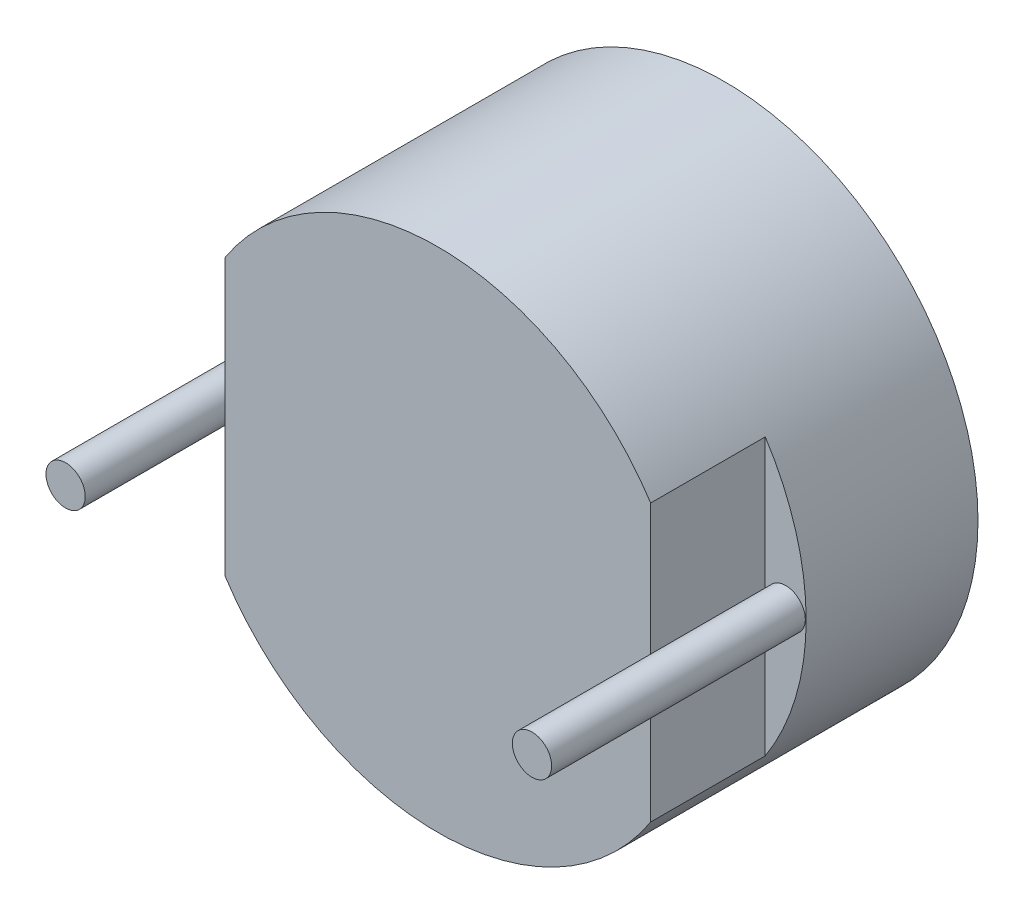
SolidWorks part; units mm, degrees
ref_plane "Front Plane" through (0, 0, 0) normal (0, 0, 1) x (1, 0, 0)
ref_plane "Top Plane" through (0, 0, 0) normal (0, 1, 0) x (1, 0, 0)
ref_plane "Right Plane" through (0, 0, 0) normal (1, 0, 0) x (0, 0, -1)
sketch "Sketch1" plane through (0, 0, 0) normal (0, 0, 1) x (1, 0, 0)
  circle A0 centre (-49.1532, 27.1636) radius 3.1
extrude "Boss-Extrude1" add sketch "Sketch1" along normal blind 3.5
sketch "Sketch2" plane through (0, 0, 3.5) normal (0, 0, 1) x (1, 0, 0)
  line L2 (-51.7532, 27.1636) -> (-51.7532, 28.8518)
  line L3 (-51.7532, 27.1636) -> (-51.7532, 25.4754)
  line L4 (-46.5532, 27.1636) -> (-46.5532, 25.4754)
  line L5 (-46.5532, 27.1636) -> (-46.5532, 28.8518)
  circle A0 centre (-49.1532, 27.1636) radius 3.1 construction
  arc A1 (-51.7532, 28.8518) -> (-51.7532, 25.4754) centre (-49.1532, 27.1636) ccw
  arc A2 (-46.5532, 25.4754) -> (-46.5532, 28.8518) centre (-49.1532, 27.1636) ccw
extrude "Cut-Extrude1" cut sketch "Sketch2" against normal blind 1.4
sketch "Sketch4" plane through (0, 0, 2.1) normal (0, 0, 1) x (1, 0, 0)
  circle A0 centre (-46.3032, 27.1636) radius 0.24
extrude "Boss-Extrude23" add sketch "Sketch4" along normal blind 3.1
sketch "Sketch5" plane through (0, 0, 2.1) normal (0, 0, 1) x (1, 0, 0)
  circle A0 centre (-52.0032, 27.1636) radius 0.24
extrude "Boss-Extrude24" add sketch "Sketch5" along normal blind 3.1
sketch "Sketch6" plane through (0, 0, 0) normal (0, 0, -1) x (-1, 0, 0)
  circle A0 centre (49.1532, 27.1636) radius 2.9
extrude "Cut-Extrude3" cut sketch "Sketch6" against normal blind 0.2
sketch "Sketch7" plane through (0, 0, 0.2) normal (0, 0, -1) x (-1, 0, 0)
  circle A0 centre (49.1532, 27.1636) radius 1.675
extrude "Boss-Extrude25" add sketch "Sketch7" along normal blind 1
